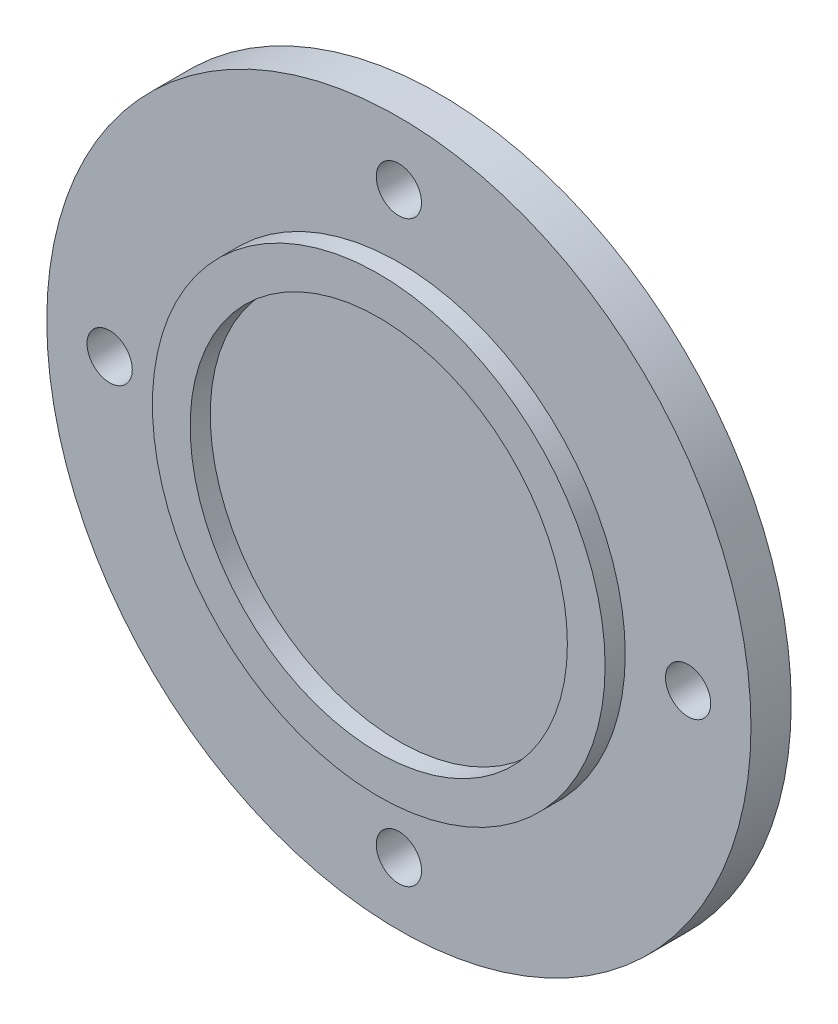
SolidWorks part; units mm, degrees
ref_plane "Front" through (0, 0, 0) normal (0, 0, 1) x (1, 0, 0)
ref_plane "Top" through (0, 0, 0) normal (0, 1, 0) x (1, 0, 0)
ref_plane "Right" through (0, 0, 0) normal (1, 0, 0) x (0, 0, -1)
sketch "Sketch1" plane through (0, 0, 0) normal (0, 0, 1) x (1, 0, 0)
  circle A0 centre (0, 0) radius 70
  circle A1 centre (0, 0) radius 57.5 construction
  circle A2 centre (0, 57.5) radius 4.5
  circle A3 centre (57.5, 0) radius 4.5
  circle A4 centre (0, -57.5) radius 4.5
  circle A5 centre (-57.5, 0) radius 4.5
  dimension "D1" = 140
  dimension "D2" = 115
  dimension "D3" = 9
  dimension "D4" = 4
extrude "Boss-Extrude1" add sketch "Sketch1" along normal blind 12
sketch "Sketch2" plane through (0, 0, 12) normal (0, 0, 1) x (1, 0, 0)
  circle A0 centre (0, 0) radius 70
  circle A1 centre (0, 0) radius 45
  dimension "D1" = 90
extrude "Cut-Extrude1" cut sketch "Sketch2" against normal blind 4
sketch "Sketch3" plane through (0, 0, 12) normal (0, 0, 1) x (1, 0, 0)
  circle A0 centre (0, 0) radius 37.5
  dimension "D1" = 75
extrude "Cut-Extrude2" cut sketch "Sketch3" against normal blind 4
